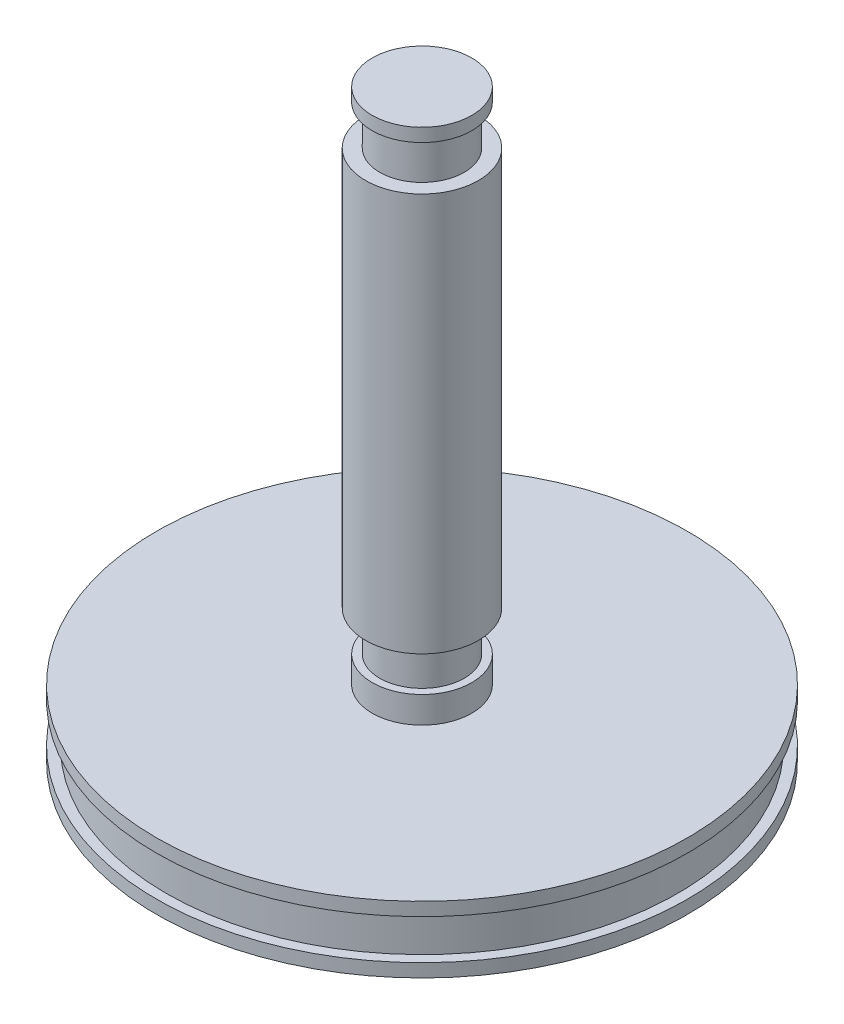
SolidWorks part; units mm, degrees
ref_plane "Front Plane" through (0, 0, 0) normal (0, 0, 1) x (1, 0, 0)
ref_plane "Top Plane" through (0, 0, 0) normal (0, 1, 0) x (1, 0, 0)
ref_plane "Right Plane" through (0, 0, 0) normal (1, 0, 0) x (0, 0, -1)
sketch "Sketch1" plane through (0, 0, 0) normal (0, 1, 0) x (1, 0, 0)
  circle A0 centre (0, 0) radius 38.515
  dimension "D1" = 77.03
extrude "Boss-Extrude1" add sketch "Sketch1" along normal blind 10
sketch "Sketch2" plane through (0, 0, 0) normal (0, -1, 0) x (1, 0, 0)
  circle A0 centre (0, 0) radius 40
  dimension "D1" = 80
extrude "Boss-Extrude2" add sketch "Sketch2" against normal blind 2
sketch "Sketch3" plane through (0, 10, 0) normal (0, 1, 0) x (1, 0, 0)
  circle A0 centre (0, 0) radius 40
  dimension "D1" = 80
extrude "Boss-Extrude3" add sketch "Sketch3" against normal blind 2
sketch "Sketch4" plane through (0, 10, 0) normal (0, 1, 0) x (1, 0, 0)
  circle A0 centre (0, 0) radius 6.366
  dimension "D1" = 12.732
extrude "Boss-Extrude4" add sketch "Sketch4" along normal blind 78
sketch "Sketch5" plane through (0, 88, 0) normal (0, 1, 0) x (1, 0, 0)
  circle A0 centre (0, 0) radius 7.5
  dimension "D1" = 15
extrude "Boss-Extrude5" add sketch "Sketch5" against normal blind 2
ref_plane "Plane1" through (0, 80, 0) normal (0, -1, 0) x (-1, 0, 0)
sketch "Sketch6" plane through (0, 80, 0) normal (0, -1, 0) x (-1, 0, 0)
  circle A0 centre (0, 0) radius 8.5
  dimension "D1" = 17
extrude "Boss-Extrude6" add sketch "Sketch6" along normal blind 60
sketch "Sketch7" plane through (0, 10, 0) normal (0, 1, 0) x (1, 0, 0)
  circle A0 centre (0, 0) radius 7.5
  dimension "D1" = 15
extrude "Boss-Extrude7" add sketch "Sketch7" along normal blind 4
